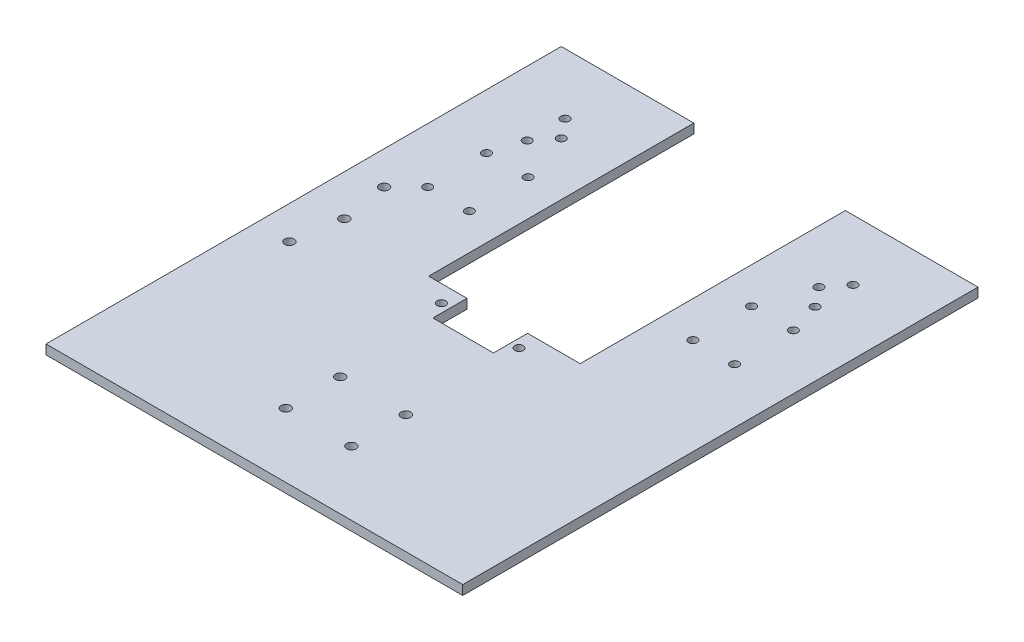
SolidWorks part; units mm, degrees
material "Acrylic (Medium-high impact)"
ref_plane "Front Plane" through (0, 0, 0) normal (0, 0, 1) x (1, 0, 0)
ref_plane "Top Plane" through (0, 0, 0) normal (0, 1, 0) x (1, 0, 0)
ref_plane "Right Plane" through (0, 0, 0) normal (1, 0, 0) x (0, 0, -1)
sketch "Sketch1" plane through (0, 0, 0) normal (0, 1, 0) x (1, 0, 0)
  line L1 (-110, 136) -> (110, 136)
  line L2 (-110, 136) -> (-110, -136)
  line L3 (-110, -136) -> (110, -136)
  line L4 (110, 136) -> (110, -136)
  line L5 (-110, 136) -> (110, -136) construction
  line L6 (-110, -136) -> (110, 136) construction
  line L7 (12.2304, -22) -> (-19.7696, -22)
  line L8 (12.2304, -22) -> (12.2304, -4)
  line L9 (12.2304, -4) -> (-19.7696, -4)
  line L10 (-19.7696, -22) -> (-19.7696, -4)
  circle A0 centre (68, 94) radius 2.25
  circle A1 centre (76, 104) radius 2.235
  circle A2 centre (76, 84) radius 2.24
  circle A4 centre (-76, 84) radius 2.25
  circle A6 centre (-68, 94) radius 2.25
  circle A8 centre (-76, 104) radius 2.25
  circle A10 centre (-81, 67.5) radius 2.25
  circle A11 centre (-81, 36.5) radius 2.25
  circle A12 centre (-59, 67.5) radius 2.25
  circle A13 centre (-59, 36.5) radius 2.25
  circle A14 centre (59, 36.5) radius 2.25
  circle A15 centre (59, 67.5) radius 2.25
  circle A16 centre (81, 67.5) radius 2.25
  circle A17 centre (81, 36.5) radius 2.25
  circle A18 centre (-24.2696, -13) radius 2.25
  circle A19 centre (16.7304, -13) radius 2.25
  circle A20 centre (-17.3151, -102.1046) radius 2.5
  circle A21 centre (17.3151, -102.1046) radius 2.5
  circle A22 centre (17.3151, -73.3689) radius 2.5
  circle A23 centre (-17.3151, -73.3689) radius 2.5
  circle A24 centre (-88.5, 0) radius 2.5
  circle A25 centre (-92.5, 25) radius 2.5
  circle A26 centre (-92.5, -25) radius 2.5
  point P0 (0, 0)
  dimension "D3" = 4.5
  dimension "D1" = 220
  dimension "D2" = 272
extrude "Boss-Extrude1" add sketch "Sketch1" along normal blind 5
sketch "Sketch3" plane through (0, 5, 0) normal (0, 1, 0) x (1, 0, 0)
  line L0 (0, 136) -> (40, 136)
  line L1 (110, 136) -> (-110, 136) construction
  line L2 (40, 136) -> (40, -4)
  line L3 (40, -4) -> (-40, -4)
  line L4 (-40, -4) -> (-40, 136)
  line L6 (-40, 136) -> (0, 136)
  line L7 (-40, 136) -> (40, -4) construction
  line L8 (0, 0) -> (0, 136) construction
  line L9 (40, 136) -> (-40, -4) construction
  dimension "D1" = 140
  dimension "D2" = 40
  dimension "D3" = 40
extrude "Cut-Extrude1" cut sketch "Sketch3" against normal through all contours L2 L3 L4 L6 L0
